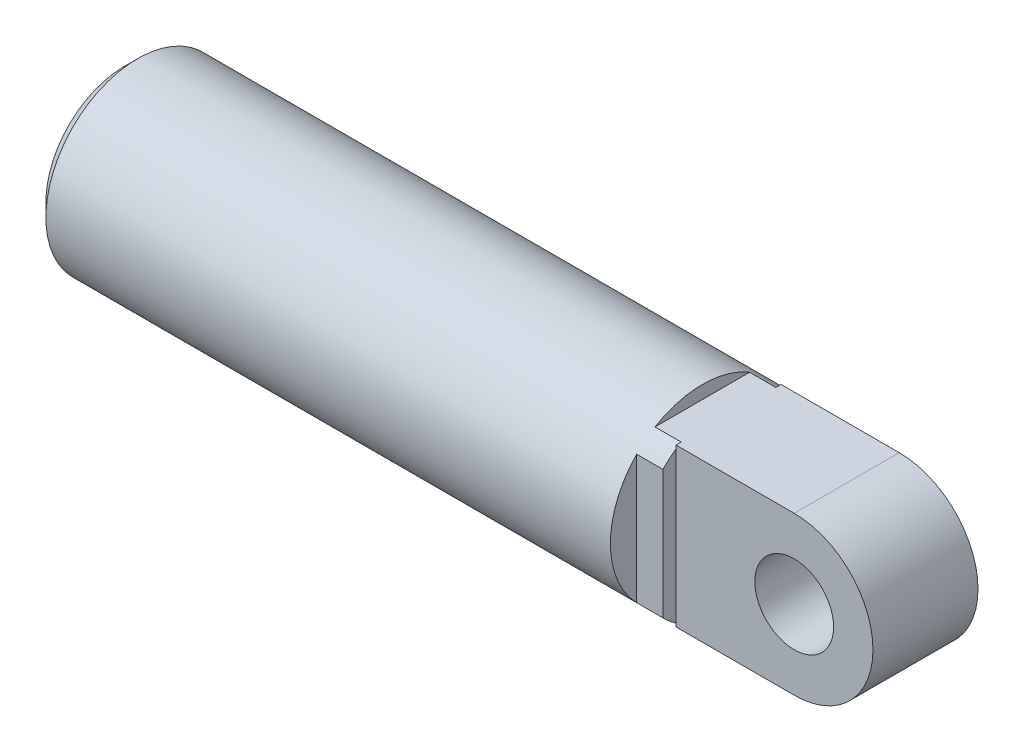
SolidWorks part; units mm, degrees
ref_plane "Front Plane" through (0, 0, 0) normal (1, 0, 0) x (0, 1, 0)
ref_plane "Top Plane" through (0, 0, 0) normal (0, 0, 1) x (0, 1, 0)
ref_plane "Right Plane" through (0, 0, 0) normal (0, 1, 0) x (-1, 0, 0)
sketch "Sketch1" plane through (0, 0, 0) normal (1, 0, 0) x (0, 1, 0)
  circle A0 centre (0, 0) radius 7
  dimension "D1" = 14
extrude "Boss-Extrude1" add sketch "Sketch1" along normal blind 44
sketch "Sketch2" plane through (44, 0, 0) normal (1, 0, 0) x (0, 1, 0)
  line L0 (-4.899, 5) -> (4.899, 5)
  line L2 (-6, 3.6056) -> (-6, -3.6056)
  line L3 (-4.899, -5) -> (4.899, -5)
  line L4 (6, 3.6056) -> (6, -3.6056)
  line L5 (-9.4179, 0) -> (8.5528, 0) construction
  line L6 (0, 7.4616) -> (0, -7.8745) construction
  arc A0 (-6, -3.6056) -> (-4.899, -5) centre (0, 0) ccw
  arc A1 (4.899, -5) -> (6, -3.6056) centre (0, 0) ccw
  arc A2 (6, 3.6056) -> (4.899, 5) centre (0, 0) ccw
  arc A3 (-4.899, 5) -> (-6, 3.6056) centre (0, 0) ccw
  point P0 (0, 0)
  dimension "D3" = 14
  dimension "D1" = 10
  dimension "D2" = 12
extrude "Boss-Extrude2" add sketch "Sketch2" along normal blind 2
sketch "Sketch3" plane through (0, 0, 0) normal (0, 0, 1) x (0, 1, 0)
  line L0 (-6, -46) -> (6, -46)
  line L1 (4.899, -46) -> (-4.899, -46) construction
  line L2 (-6, -46) -> (-6, -55)
  line L4 (6, -55) -> (6, -46)
  arc A0 (-6, -55) -> (6, -55) centre (0, -55) ccw
  circle A1 centre (0, -55) radius 3
  point P5 (0, -46)
  dimension "D3" = 6
  dimension "D1" = 12
  dimension "D2" = 9
extrude "Boss-Extrude3" add sketch "Sketch3" along normal mid plane 8
sketch "Sketch4" plane through (0, 0, 0) normal (-1, 0, 0) x (0, -1, 0)
  point P0 (0, 0)
hole_wizard "Tap Drill for M5 Tap1" positions "Sketch4" profile "Sketch5" hole size "M5" standard "ISO"
sketch "Sketch5" plane through (0, 0, 0) normal (0, 1, 0) x (0, 0, 1)
  line L0 (0, 0) -> (0, 16.2618)
  line L1 (0, 16.2618) -> (2.1, 15)
  line L2 (2.1, 15) -> (2.1, 0)
  line L5 (2.1, 0) -> (0, 0)
  line L10 (0, 16.2618) -> (-2.1, 15) construction
  line L11 (0, -6.35) -> (0, 107.95) construction
  dimension "Hole Dia." = 4.2
  dimension "Hole Depth" = 15
  dimension "Drill Angle" = 118
chamfer "Chamfer1" distance 1 angle 45 1 edges at (0, 0, -7)
